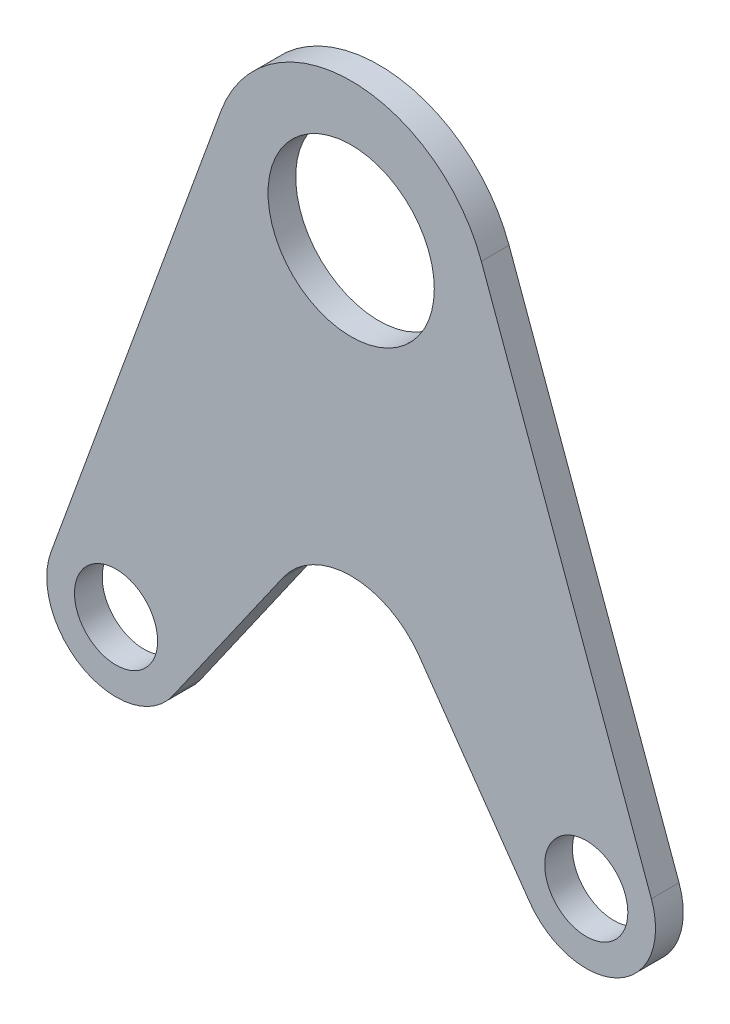
SolidWorks part; units mm, degrees
ref_plane "Front Plane" through (0, 0, 0) normal (0, 0, 1) x (1, 0, 0)
ref_plane "Top Plane" through (0, 0, 0) normal (0, 1, 0) x (1, 0, 0)
ref_plane "Right Plane" through (0, 0, 0) normal (1, 0, 0) x (0, 0, -1)
sketch "Sketch1" plane through (0, 0, 0) normal (0, 0, 1) x (1, 0, 0)
  line L0 (-46.9846, 17.101) -> (-108.332, -151.4495)
  line L1 (46.9846, 17.101) -> (108.332, -151.4495)
  line L2 (-64.3609, -174.3394) -> (-24.5746, -117.5187)
  line L3 (24.5746, -117.5187) -> (64.3609, -174.3394)
  line L4 (0, 0) -> (0, -134.726) construction
  line L5 (0, -134.726) -> (0, -136.1956) construction
  circle A0 centre (0, 0) radius 30
  arc A1 (46.9846, 17.101) -> (-46.9846, 17.101) centre (0, 0) ccw
  circle A2 centre (-84.8397, -160) radius 15
  arc A3 (-108.332, -151.4495) -> (-64.3609, -174.3394) centre (-84.8397, -160) ccw
  circle A4 centre (84.8397, -160) radius 15
  arc A5 (64.3609, -174.3394) -> (108.332, -151.4495) centre (84.8397, -160) ccw
  arc A6 (-24.5746, -117.5187) -> (24.5746, -117.5187) centre (0, -134.726) cw
  point P18 (0, 0)
  dimension "D1" = 30
  dimension "D2" = 50
  dimension "D3" = 60
  dimension "D4" = 100
  dimension "D6" = 30
  dimension "D8" = 160
  dimension "D5" = 20
  dimension "D7" = 35
  dimension "D9" = 35
extrude "Boss-Extrude1" add sketch "Sketch1" along normal blind 10
